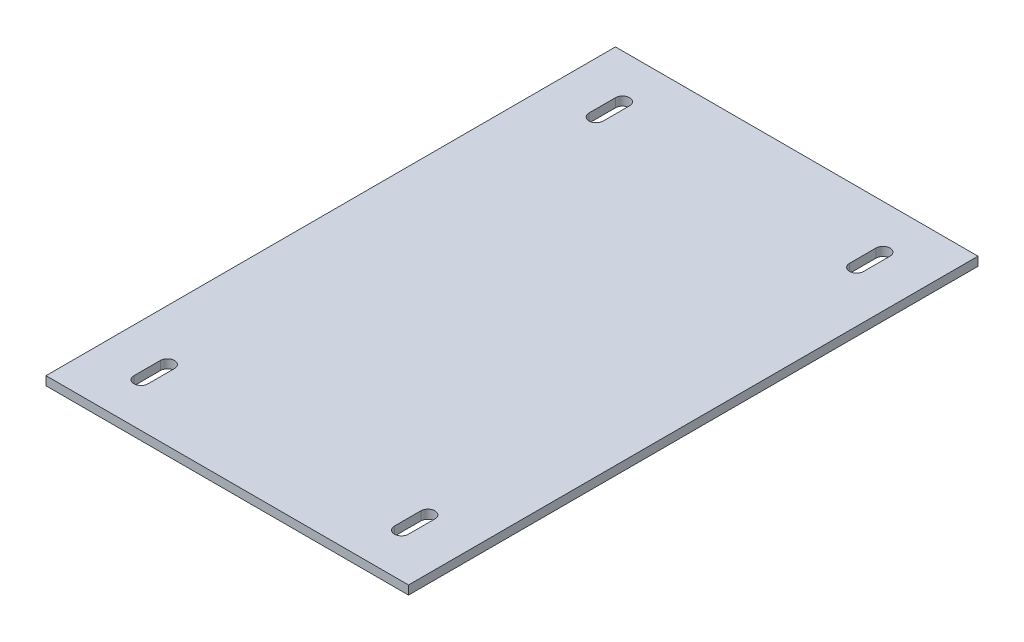
SolidWorks part; units mm, degrees
ref_plane "Front Plane" through (0, 0, 0) normal (0, 0, 1) x (1, 0, 0)
ref_plane "Top Plane" through (0, 0, 0) normal (0, 1, 0) x (1, 0, 0)
ref_plane "Right Plane" through (0, 0, 0) normal (1, 0, 0) x (0, 0, -1)
sketch "Sketch1" plane through (0, 0, 0) normal (0, 1, 0) x (1, 0, 0)
  line L0 (25, 298.61) -> (25, 283.61)
  line L1 (0, 0) -> (206, 0)
  line L2 (0, 0) -> (0, 323.61)
  line L3 (0, 323.61) -> (206, 323.61)
  line L4 (206, 0) -> (206, 323.61)
  line L5 (33, 298.61) -> (33, 283.61)
  line L6 (103, 323.61) -> (103, 0) construction
  line L7 (0, 161.805) -> (206, 161.805) construction
  line L8 (25, 25) -> (25, 40)
  line L9 (33, 25) -> (33, 40)
  line L10 (173, 25) -> (173, 40)
  line L11 (181, 25) -> (181, 40)
  line L12 (173, 298.61) -> (173, 283.61)
  line L13 (181, 298.61) -> (181, 283.61)
  arc A0 (33, 298.61) -> (25, 298.61) centre (29, 298.61) ccw
  arc A1 (25, 283.61) -> (33, 283.61) centre (29, 283.61) ccw
  arc A2 (25, 40) -> (33, 40) centre (29, 40) cw
  arc A3 (33, 25) -> (25, 25) centre (29, 25) cw
  arc A4 (173, 25) -> (181, 25) centre (177, 25) ccw
  arc A5 (181, 40) -> (173, 40) centre (177, 40) ccw
  arc A6 (181, 283.61) -> (173, 283.61) centre (177, 283.61) cw
  arc A7 (173, 298.61) -> (181, 298.61) centre (177, 298.61) cw
  dimension "D3" = 8
  dimension "D4" = 8
  dimension "D6" = 15
  dimension "D7" = 25
  dimension "D1" = 323.61
  dimension "D2" = 206
  dimension "D5" = 25
extrude "Boss-Extrude1" add sketch "Sketch1" along normal blind 5
